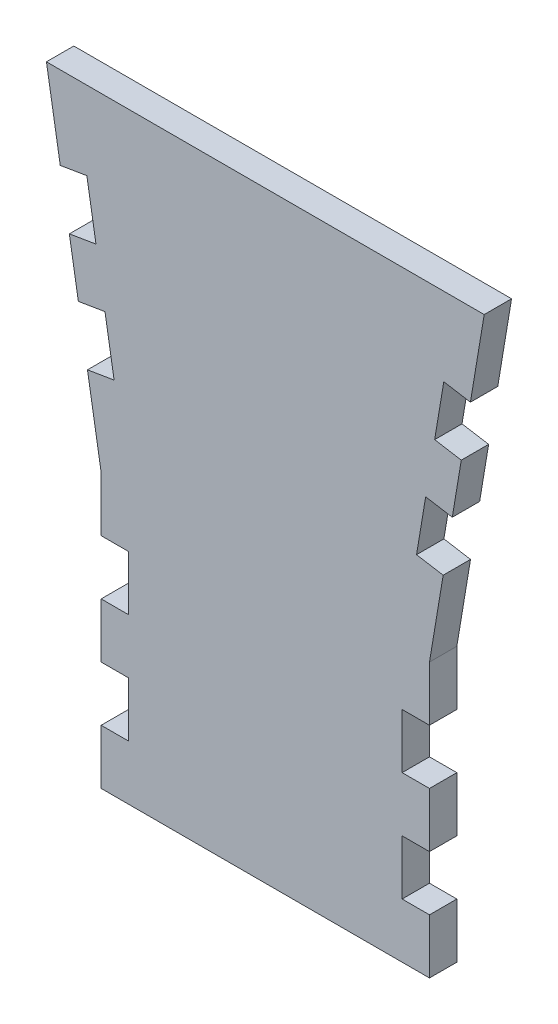
SolidWorks part; units mm, degrees
ref_plane "Plan de face" through (0, 0, 0) normal (0, 0, 1) x (1, 0, 0)
ref_plane "Plan de dessus" through (0, 0, 0) normal (0, 1, 0) x (1, 0, 0)
ref_plane "Plan de droite" through (0, 0, 0) normal (1, 0, 0) x (0, 0, -1)
sketch "Model" plane through (0, 0, 0) normal (0, 0, 1) x (1, 0, 0)
  line L0 (-23.8235, 20) -> (-18.8235, 20)
  line L1 (-23.8235, 30) -> (-23.8235, 20)
  line L2 (-23.8235, 30) -> (-18.8235, 30)
  line L3 (-18.8235, 40) -> (-18.8235, 30)
  line L4 (-23.8235, 40) -> (-18.8235, 40)
  line L5 (-23.8235, 50) -> (-23.8235, 40)
  line L6 (-26.3235, 65) -> (-23.8235, 50)
  line L7 (-26.3235, 65) -> (-21.4587, 65.8108)
  line L8 (-23.1253, 75.8108) -> (-21.4587, 65.8108)
  line L9 (-27.9902, 75) -> (-23.1253, 75.8108)
  line L10 (-27.9902, 75) -> (-29.6342, 84.8639)
  line L11 (-29.6342, 84.8639) -> (-24.7693, 85.6748)
  line L12 (-26.436, 95.6748) -> (-24.7693, 85.6748)
  line L13 (-31.3009, 94.8639) -> (-26.436, 95.6748)
  line L14 (-31.3009, 94.8639) -> (-33.8235, 110)
  line L15 (-33.8235, 110) -> (46.1765, 110)
  line L16 (43.6538, 94.8639) -> (46.1765, 110)
  line L17 (43.6538, 94.8639) -> (38.7889, 95.6748)
  line L18 (38.7889, 95.6748) -> (37.1223, 85.6748)
  line L19 (41.9871, 84.8639) -> (37.1223, 85.6748)
  line L20 (40.3431, 75) -> (41.9871, 84.8639)
  line L21 (40.3431, 75) -> (35.4783, 75.8108)
  line L22 (35.4783, 75.8108) -> (33.8116, 65.8108)
  line L23 (38.6765, 65) -> (33.8116, 65.8108)
  line L24 (38.6765, 65) -> (36.1765, 50)
  line L25 (36.1765, 50) -> (36.1765, 40)
  line L26 (36.1765, 40) -> (31.1765, 40)
  line L27 (31.1765, 40) -> (31.1765, 30)
  line L28 (36.1765, 30) -> (31.1765, 30)
  line L29 (36.1765, 30) -> (36.1765, 20)
  line L30 (36.1765, 20) -> (31.1765, 20)
  line L31 (31.1765, 20) -> (31.1765, 10)
  line L32 (36.1765, 10) -> (31.1765, 10)
  line L33 (36.1765, 10) -> (36.1765, 0)
  line L34 (36.1765, 0) -> (-23.8235, 0)
  line L35 (-23.8235, 10) -> (-23.8235, 0)
  line L36 (-23.8235, 10) -> (-18.8235, 10)
  line L37 (-18.8235, 20) -> (-18.8235, 10)
extrude "Boss.-Extru.1" add sketch "Model" along normal blind 5
